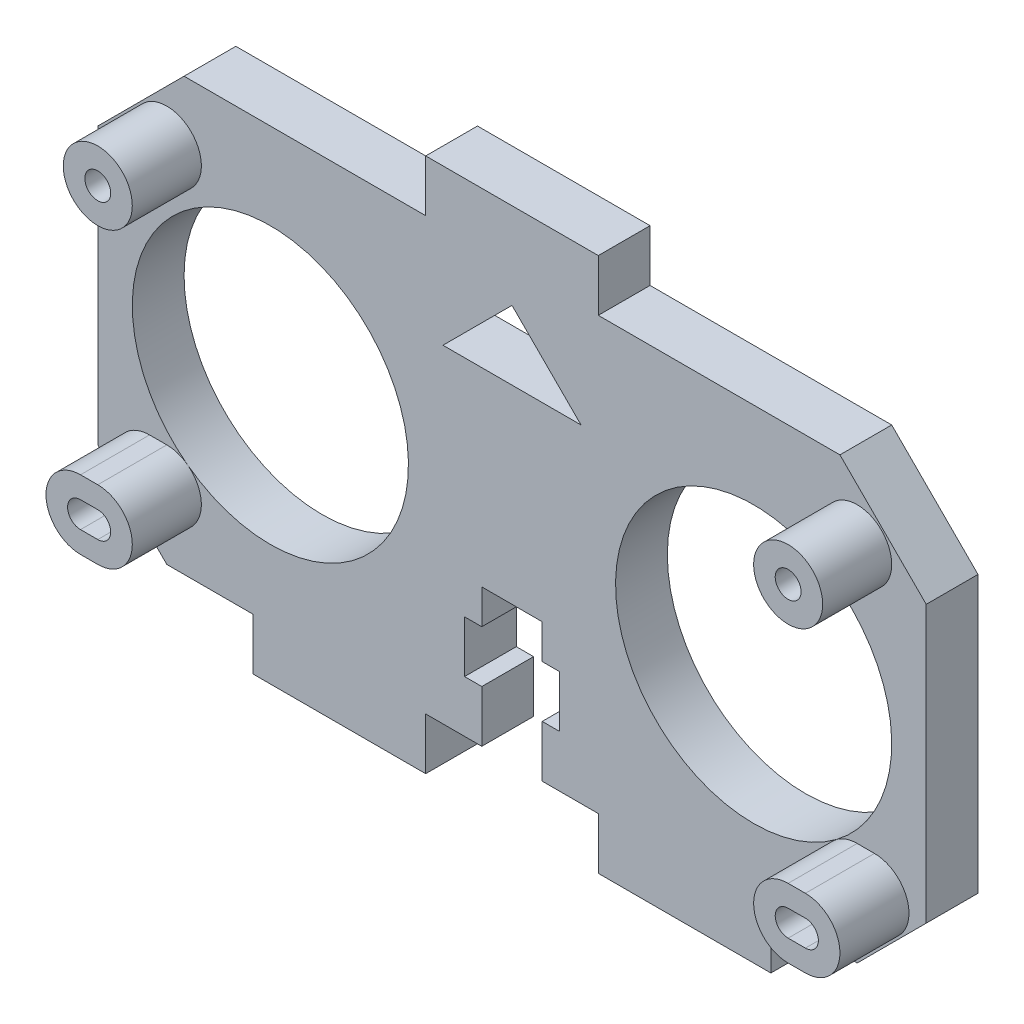
SolidWorks part; units mm, degrees
ref_plane "Plan de face" through (0, 0, 0) normal (0, 0, 1) x (1, 0, 0)
ref_plane "Plan de dessus" through (0, 0, 0) normal (0, 1, 0) x (1, 0, 0)
ref_plane "Plan de droite" through (0, 0, 0) normal (1, 0, 0) x (0, 0, -1)
sketch "Esquisse1" plane through (0, 0, 0) normal (0, 0, 1) x (1, 0, 0)
  line L1 (0, 0) -> (48, 0)
  line L2 (0, 0) -> (0, 31)
  line L3 (0, 31) -> (48, 31)
  line L4 (48, 0) -> (48, 31)
  dimension "D1" = 31
  dimension "D2" = 48
extrude "Boss.-Extru.1" add sketch "Esquisse1" along normal blind 3
sketch "Esquisse3" plane through (0, 0, 3) normal (0, 0, 1) x (1, 0, 0)
  line L0 (0, 0) -> (48, 0) construction
  line L1 (19, 0) -> (29, 0)
  line L2 (19, 0) -> (19, 3)
  line L3 (19, 3) -> (29, 3)
  line L4 (29, 0) -> (29, 3)
  line L5 (0, 31) -> (0, 0) construction
  point P6 (24, 0)
  dimension "D1" = 10
  dimension "D2" = 3
  dimension "D3" = 24
extrude "Enlèv. mat.-Extru.2" cut sketch "Esquisse3" against normal up to next contours L3 L4 L1 L2
sketch "Esquisse4" plane through (0, 0, 3) normal (0, 0, 1) x (1, 0, 0)
  line L0 (0, 31) -> (0, 0) construction
  line L1 (21.25, 9) -> (26.75, 9)
  line L2 (21.25, 9) -> (21.25, 6)
  line L3 (21.25, 6) -> (26.75, 6)
  line L4 (26.75, 9) -> (26.75, 6)
  line L5 (48, 31) -> (0, 31) construction
  point P4 (24, 6)
  dimension "D1" = 5.5
  dimension "D2" = 3
  dimension "D3" = 24
  dimension "D4" = 22
extrude "Enlèv. mat.-Extru.3" cut sketch "Esquisse4" against normal up to next
sketch "Esquisse5" plane through (0, 0, 3) normal (0, 0, 1) x (1, 0, 0)
  line L1 (22.25, 11) -> (25.75, 11)
  line L2 (22.25, 11) -> (22.25, 0)
  line L3 (22.25, 0) -> (25.75, 0)
  line L4 (25.75, 11) -> (25.75, 0)
  point P4 (24, 0)
  dimension "D1" = 24
  dimension "D2" = 11
  dimension "D3" = 3.5
extrude "Enlèv. mat.-Extru.4" cut sketch "Esquisse5" against normal up to next contours L1 L4 L3 L2
sketch "Esquisse8" plane through (0, 0, 3) normal (0, 0, 1) x (1, 0, 0)
  line L1 (0, 0) -> (5, 0)
  line L2 (0, 0) -> (0, 3)
  line L3 (0, 3) -> (5, 3)
  line L4 (5, 0) -> (5, 3)
  dimension "D1" = 5
  dimension "D2" = 3
extrude "Enlèv. mat.-Extru.7" cut sketch "Esquisse8" against normal up to next
sketch "Esquisse9" plane through (0, 0, 3) normal (0, 0, 1) x (1, 0, 0)
  line L1 (48, 0) -> (43, 0)
  line L2 (48, 0) -> (48, 3)
  line L3 (48, 3) -> (43, 3)
  line L4 (43, 0) -> (43, 3)
  dimension "D1" = 5
  dimension "D2" = 3
extrude "Enlèv. mat.-Extru.8" cut sketch "Esquisse9" against normal up to next contours L3 L4 L1 L2
sketch "Esquisse18" plane through (0, 0, 3) normal (0, 0, 1) x (1, 0, 0)
  line L1 (43, 0) -> (39, 0)
  line L2 (43, 0) -> (43, 3)
  line L3 (43, 3) -> (39, 3)
  line L4 (39, 0) -> (39, 3)
  dimension "D1" = 3
  dimension "D2" = 4
extrude "Enlèv. mat.-Extru.14" cut sketch "Esquisse18" against normal up to next
sketch "Esquisse23" plane through (0, 0, 3) normal (0, 0, 1) x (1, 0, 0)
  line L1 (5, 0) -> (9, 0)
  line L2 (5, 0) -> (5, 3)
  line L3 (5, 3) -> (9, 3)
  line L4 (9, 0) -> (9, 3)
  dimension "D1" = 4
  dimension "D2" = 3
extrude "Enlèv. mat.-Extru.19" cut sketch "Esquisse23" against normal up to next contours L3 L4 L1 L2
sketch "Esquisse24" plane through (0, 0, 3) normal (0, 0, 1) x (1, 0, 0)
  line L0 (20, 22) -> (24, 26)
  line L1 (24, 26) -> (28, 22)
  line L2 (28, 22) -> (20, 22)
  line L3 (0, 31) -> (0, 3) construction
  line L4 (48, 31) -> (0, 31) construction
  point P3 (24, 22)
  dimension "D1" = 24
  dimension "D2" = 8
  dimension "D3" = 4
  dimension "D4" = 5
extrude "Enlèv. mat.-Extru.20" cut sketch "Esquisse24" against normal up to next contours L0 L1 L2
sketch "Esquisse25" plane through (0, 0, 3) normal (0, 0, 1) x (1, 0, 0)
  line L1 (48, 31) -> (29, 31)
  line L2 (48, 31) -> (48, 28)
  line L3 (48, 28) -> (29, 28)
  line L4 (29, 31) -> (29, 28)
  dimension "D1" = 19
  dimension "D2" = 3
extrude "Enlèv. mat.-Extru.21" cut sketch "Esquisse25" against normal up to next contours L3 L4 L1 L2
sketch "Esquisse26" plane through (0, 0, 3) normal (0, 0, 1) x (1, 0, 0)
  line L1 (0, 31) -> (19, 31)
  line L2 (0, 31) -> (0, 28)
  line L3 (0, 28) -> (19, 28)
  line L4 (19, 31) -> (19, 28)
  dimension "D1" = 19
  dimension "D2" = 3
extrude "Enlèv. mat.-Extru.22" cut sketch "Esquisse26" against normal up to next contours L3 L4 L1 L2
sketch "Esquisse27" plane through (0, 0, 3) normal (0, 0, 1) x (1, 0, 0)
  line L0 (48, 3) -> (48, 28) construction
  line L1 (29, 0) -> (39, 0) construction
  circle A0 centre (38, 15) radius 8
  dimension "D1" = 16
  dimension "D2" = 10
  dimension "D3" = 15
extrude "Enlèv. mat.-Extru.23" cut sketch "Esquisse27" against normal up to next contours A0
sketch "Esquisse28" plane through (0, 0, 3) normal (0, 0, 1) x (1, 0, 0)
  line L0 (0, 28) -> (0, 3) construction
  line L1 (9, 0) -> (19, 0) construction
  circle A0 centre (10, 15) radius 8
  dimension "D1" = 16
  dimension "D2" = 10
  dimension "D3" = 15
extrude "Enlèv. mat.-Extru.24" cut sketch "Esquisse28" against normal up to next contours A0
sketch "Esquisse29" plane through (0, 0, 3) normal (0, 0, 1) x (1, 0, 0)
  line L0 (0, 28) -> (19, 28) construction
  line L1 (0, 28) -> (0, 3) construction
  circle A0 centre (4, 24) radius 2
  dimension "D1" = 4
  dimension "D2" = 4
  dimension "D3" = 4
extrude "Boss.-Extru.5" add sketch "Esquisse29" along normal blind 4 contours A0
sketch "Esquisse30" plane through (0, 0, 3) normal (0, 0, 1) x (1, 0, 0)
  line L0 (48, 28) -> (29, 28) construction
  line L1 (48, 3) -> (48, 28) construction
  circle A0 centre (44, 24) radius 2
  dimension "D3" = 4
  dimension "D1" = 4
  dimension "D2" = 4
extrude "Boss.-Extru.6" add sketch "Esquisse30" along normal blind 4
sketch "Esquisse31" plane through (0, 0, 7) normal (0, 0, 1) x (1, 0, 0)
  line L0 (0, 28) -> (19, 28) construction
  line L1 (0, 28) -> (0, 3) construction
  circle A0 centre (4, 24) radius 0.75
  dimension "D3" = 1.5
  dimension "D1" = 4
  dimension "D2" = 4
extrude "Enlèv. mat.-Extru.25" cut sketch "Esquisse31" against normal up to next
sketch "Esquisse32" plane through (0, 0, 7) normal (0, 0, 1) x (1, 0, 0)
  line L0 (48, 3) -> (48, 28) construction
  line L1 (48, 28) -> (29, 28) construction
  circle A0 centre (44, 24) radius 0.75
  dimension "D3" = 1.5
  dimension "D1" = 4
  dimension "D2" = 4
extrude "Enlèv. mat.-Extru.26" cut sketch "Esquisse32" against normal up to next
sketch "Esquisse33" plane through (0, 0, 3) normal (0, 0, 1) x (1, 0, 0)
  line L0 (3, 7) -> (4, 7) construction
  line L1 (3, 9) -> (4, 9)
  line L2 (3, 5) -> (4, 5)
  line L3 (0, 3) -> (9, 3) construction
  line L4 (0, 28) -> (0, 3) construction
  arc A0 (3, 9) -> (3, 5) centre (3, 7) ccw
  arc A1 (4, 5) -> (4, 9) centre (4, 7) ccw
  point P2 (3.5, 7)
  dimension "D1" = 4
  dimension "D2" = 3
  dimension "D3" = 4
  dimension "D4" = 1
extrude "Boss.-Extru.7" add sketch "Esquisse33" along normal blind 4 contours L1 A1 L2 A0
sketch "Esquisse34" plane through (0, 0, 3) normal (0, 0, 1) x (1, 0, 0)
  line L0 (44, 7) -> (45, 7) construction
  line L1 (44, 9) -> (45, 9)
  line L2 (44, 5) -> (45, 5)
  line L3 (48, 3) -> (39, 3) construction
  line L4 (48, 3) -> (48, 28) construction
  arc A0 (44, 9) -> (44, 5) centre (44, 7) ccw
  arc A1 (45, 5) -> (45, 9) centre (45, 7) ccw
  point P2 (44.5, 7)
  dimension "D1" = 4
  dimension "D2" = 3
  dimension "D3" = 4
  dimension "D4" = 1
extrude "Boss.-Extru.8" add sketch "Esquisse34" along normal blind 4 contours L2 A1 L1 A0
sketch "Esquisse35" plane through (0, 0, 7) normal (0, 0, 1) x (1, 0, 0)
  line L0 (3, 7) -> (4, 7) construction
  line L1 (3, 7.75) -> (4, 7.75)
  line L2 (3, 6.25) -> (4, 6.25)
  line L3 (0, 28) -> (0, 3) construction
  line L4 (0, 3) -> (9, 3) construction
  arc A0 (3, 7.75) -> (3, 6.25) centre (3, 7) ccw
  arc A1 (4, 6.25) -> (4, 7.75) centre (4, 7) ccw
  point P2 (3.5, 7)
  dimension "D1" = 3
  dimension "D2" = 4
  dimension "D3" = 1.5
  dimension "D4" = 1
extrude "Enlèv. mat.-Extru.27" cut sketch "Esquisse35" against normal up to next contours L1 A1 L2 A0
sketch "Esquisse37" plane through (0, 0, 7) normal (0, 0, 1) x (1, 0, 0)
  line L0 (44, 7) -> (45, 7) construction
  line L1 (44, 7.75) -> (45, 7.75)
  line L2 (44, 6.25) -> (45, 6.25)
  line L3 (48, 3) -> (48, 28) construction
  line L4 (48, 3) -> (39, 3) construction
  arc A0 (44, 7.75) -> (44, 6.25) centre (44, 7) ccw
  arc A1 (45, 6.25) -> (45, 7.75) centre (45, 7) ccw
  point P2 (44.5, 7)
  dimension "D1" = 3
  dimension "D2" = 4
  dimension "D3" = 1
  dimension "D4" = 1.5
extrude "Enlèv. mat.-Extru.29" cut sketch "Esquisse37" against normal up to next contours L1 A1 L2 A0
chamfer "Chanfrein4" distance 5 angle 45 2 edges at (0, 28, 1.5) (48, 28, 1.5)
chamfer "Chanfrein5" distance 4 angle 45 2 edges at (0, 3, 1.5) (48, 3, 1.5)
